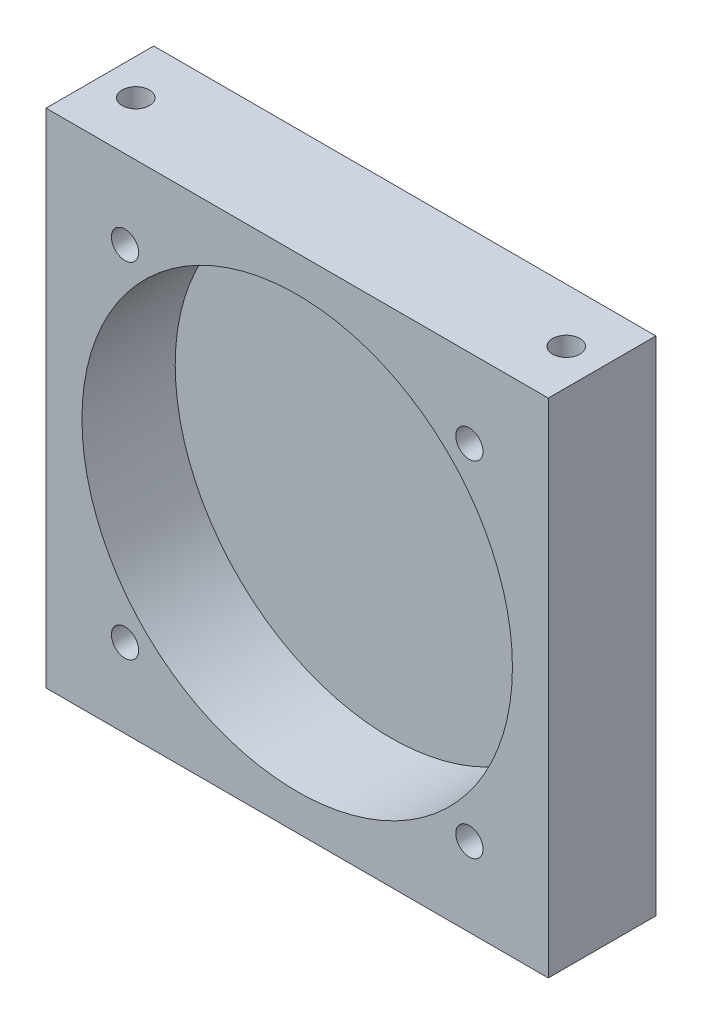
SolidWorks part; units mm, degrees
ref_plane "Front Plane" through (0, 0, 0) normal (0, 0, 1) x (1, 0, 0)
ref_plane "Top Plane" through (0, 0, 0) normal (0, 1, 0) x (1, 0, 0)
ref_plane "Right Plane" through (0, 0, 0) normal (1, 0, 0) x (0, 0, -1)
sketch "Sketch1" plane through (0, 0, 0) normal (0, 0, 1) x (1, 0, 0)
  line L1 (44.45, -44.45) -> (-44.45, -44.45)
  line L2 (44.45, -44.45) -> (44.45, 44.45)
  line L3 (44.45, 44.45) -> (-44.45, 44.45)
  line L4 (-44.45, -44.45) -> (-44.45, 44.45)
  line L5 (44.45, -44.45) -> (-44.45, 44.45) construction
  line L6 (44.45, 44.45) -> (-44.45, -44.45) construction
  point P0 (0, 0)
  dimension "D1" = 88.9
  dimension "D2" = 88.9
extrude "Boss-Extrude1" add sketch "Sketch1" along normal blind 19.05
sketch "Sketch2" plane through (0, 0, 19.05) normal (0, 0, 1) x (1, 0, 0)
  circle A0 centre (0, 0) radius 38.1
  dimension "D1" = 76.2
extrude "Cut-Extrude1" cut sketch "Sketch2" against normal blind 16.51
hole_wizard "#10-32 Tapped Hole1" positions "Sketch4" profile "Sketch3" tap size "#10-32" standard "Ansi Inch"
sketch "Sketch4" plane through (0, 44.45, 0) normal (0, 1, 0) x (-1, 0, 0)
  line L0 (-38.1, 9.525) -> (0, 0) construction
  line L1 (0, 0) -> (38.1, 9.525) construction
  line L3 (-44.45, 0) -> (44.45, 0) construction
  point P0 (38.1, 9.525)
  point P1 (-38.1, 9.525)
  dimension "D1" = 76.2
  dimension "D2" = 9.525
sketch "Sketch3" plane through (-38.1, 44.45, 9.525) normal (1, 0, 0) x (0, 0, 1)
  line L0 (0, 0) -> (0, 22.6408)
  line L1 (0, 22.6408) -> (2.0193, 21.4274)
  line L2 (2.0193, 21.4274) -> (2.0193, 19.05)
  line L3 (2.0193, 19.05) -> (2.413, 19.05)
  line L4 (2.413, 19.05) -> (2.413, 0)
  line L5 (2.413, 0) -> (0, 0)
  line L10 (0, 22.6408) -> (-2.0193, 21.4274) construction
  line L11 (0, -6.35) -> (0, 107.95) construction
  dimension "Tap Drill Dia." = 4.0386
  dimension "Tap Drill Depth" = 21.4274
  dimension "Thread Major Dia." = 4.826
  dimension "Thread Depth" = 19.05
  dimension "Drill Angle" = 118
mirror "Mirror1" about plane through (0, 0, 0) normal (0, 1, 0) of "#10-32 Tapped Hole1"
hole_wizard "#10-32 Tapped Hole2" positions "Sketch6" profile "Sketch5" tap size "#10-32" standard "Ansi Inch"
sketch "Sketch6" plane through (0, 0, 19.05) normal (0, 0, 1) x (1, 0, 0)
  line L0 (30.48, -30.48) -> (-30.48, 30.48) construction
  line L3 (30.48, 30.48) -> (-30.48, -30.48) construction
  point P0 (30.48, -30.48)
  point P1 (-30.48, -30.48)
  point P3 (-30.48, 30.48)
  point P5 (30.48, 30.48)
  dimension "D1" = 60.96
  dimension "D2" = 60.96
sketch "Sketch5" plane through (30.48, -30.48, 19.05) normal (1, 0, 0) x (0, -1, 0)
  line L0 (0, 0) -> (0, 16.1993)
  line L1 (0, 16.1993) -> (2.0193, 14.986)
  line L2 (2.0193, 14.986) -> (2.0193, 12.7)
  line L3 (2.0193, 12.7) -> (2.413, 12.7)
  line L4 (2.413, 12.7) -> (2.413, 0)
  line L5 (2.413, 0) -> (0, 0)
  line L10 (0, 16.1993) -> (-2.0193, 14.986) construction
  line L11 (0, -6.35) -> (0, 107.95) construction
  dimension "Tap Drill Dia." = 4.0386
  dimension "Tap Drill Depth" = 14.986
  dimension "Thread Major Dia." = 4.826
  dimension "Thread Depth" = 12.7
  dimension "Drill Angle" = 118
